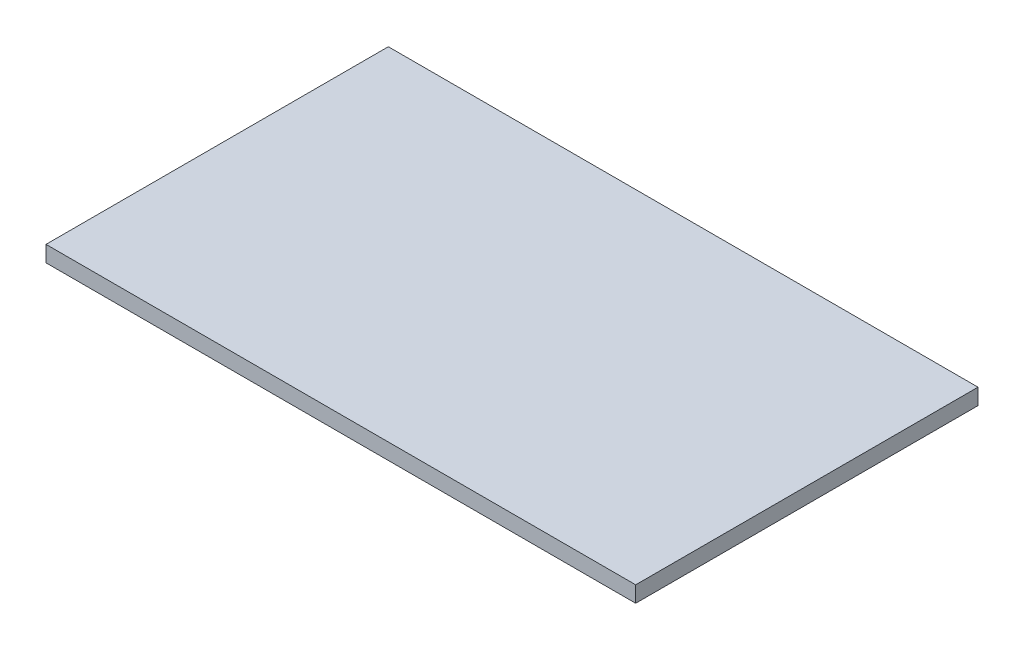
SolidWorks part; units mm, degrees
ref_plane "Front Plane" through (0, 0, 0) normal (0, 0, 1) x (1, 0, 0)
ref_plane "Top Plane" through (0, 0, 0) normal (0, 1, 0) x (1, 0, 0)
ref_plane "Right Plane" through (0, 0, 0) normal (1, 0, 0) x (0, 0, -1)
sketch "Sketch1" plane through (0, 0, 0) normal (0, 1, 0) x (1, 0, 0)
  line L1 (0, 0) -> (-26.7, 0)
  line L2 (0, 0) -> (0, 15.5)
  line L3 (0, 15.5) -> (-26.7, 15.5)
  line L4 (-26.7, 0) -> (-26.7, 15.5)
  dimension "D1" = 26.7
  dimension "D2" = 15.5
extrude "Boss-Extrude1" add sketch "Sketch1" along normal blind 0.725
